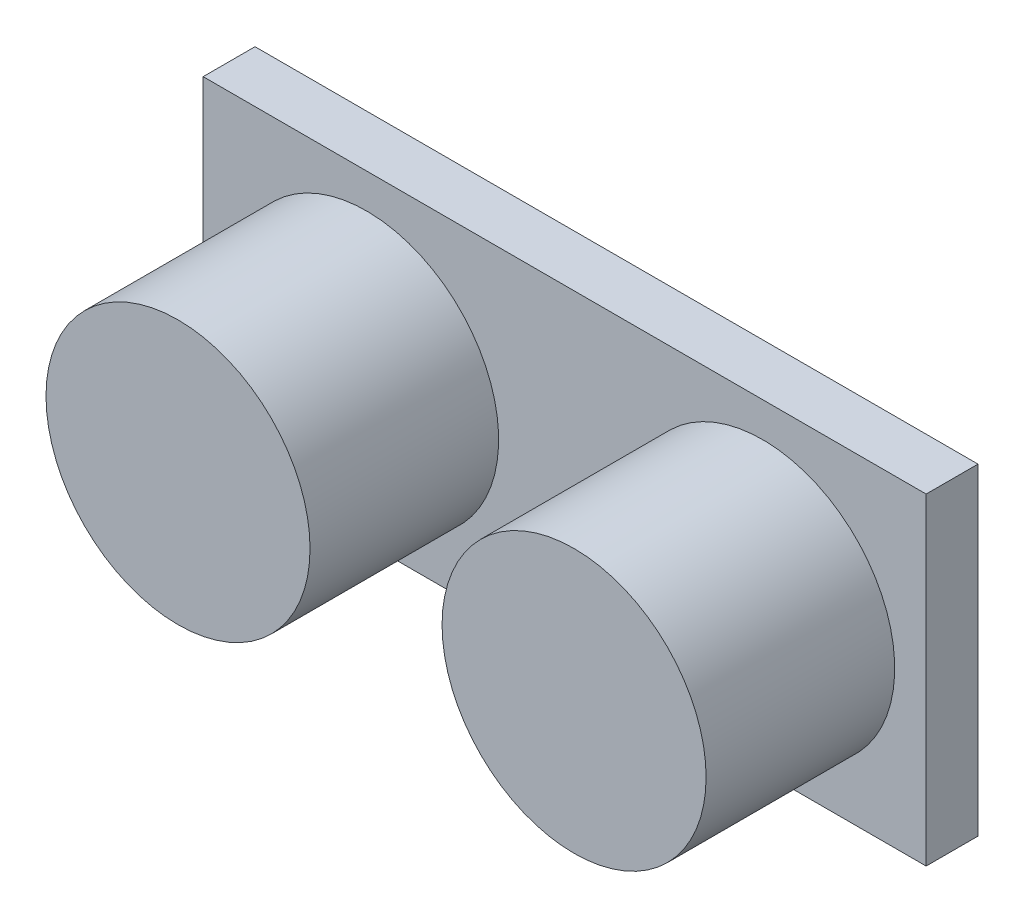
SolidWorks part; units mm, degrees
ref_plane "Front Plane" through (0, 0, 0) normal (0, 0, 1) x (1, 0, 0)
ref_plane "Top Plane" through (0, 0, 0) normal (0, 1, 0) x (1, 0, 0)
ref_plane "Right Plane" through (0, 0, 0) normal (1, 0, 0) x (0, 0, -1)
sketch "Sketch1" plane through (0, 0, 0) normal (0, 0, 1) x (1, 0, 0)
  line L1 (-23, -10.25) -> (23, -10.25)
  line L2 (-23, -10.25) -> (-23, 10.25)
  line L3 (-23, 10.25) -> (23, 10.25)
  line L4 (23, -10.25) -> (23, 10.25)
  line L5 (-23, -10.25) -> (23, 10.25) construction
  line L6 (-23, 10.25) -> (23, -10.25) construction
  point P0 (0, 0)
  dimension "D1" = 46
  dimension "D2" = 20.5
extrude "Boss-Extrude1" add sketch "Sketch1" along normal blind 3.3
sketch "Sketch2" plane through (0, 0, 3.3) normal (0, 0, 1) x (1, 0, 0)
  line L0 (-23, -0.35) -> (23, -0.35) construction
  line L1 (-23, 10.25) -> (-23, -10.25) construction
  line L2 (23, -10.25) -> (23, 10.25) construction
  line L3 (0, 0) -> (0, -0.35) construction
  line L4 (-12.6, -0.35) -> (0, 0) construction
  line L5 (0, 0) -> (12.6, -0.35) construction
  line L6 (23, 10.25) -> (-23, 10.25) construction
  circle A0 centre (-12.6, -0.35) radius 8.4
  circle A1 centre (12.6, -0.35) radius 8.4
  dimension "D1" = 25.2
  dimension "D2" = 16.8
  dimension "D3" = 10.6
extrude "Boss-Extrude2" add sketch "Sketch2" along normal blind 12
sketch "Sketch3" plane through (0, 0, 0) normal (0, 0, -1) x (-1, 0, 0)
  line L0 (0, 0) -> (0, -10.25) construction
  line L1 (23, -10.25) -> (-23, -10.25) construction
  line L2 (0, -10.25) -> (-2.6069, -14.263) construction
  line L4 (-5.15, -10.25) -> (5.15, -10.25)
  line L5 (-5.15, -10.25) -> (-5.15, -7.71)
  line L6 (-5.15, -7.71) -> (5.15, -7.71)
  line L7 (5.15, -10.25) -> (5.15, -7.71)
  line L8 (-5.15, -10.25) -> (5.15, -7.71) construction
  line L9 (-5.15, -7.71) -> (5.15, -10.25) construction
  point P5 (0, -8.98)
  dimension "D1" = 2.54
  dimension "D2" = 10.3
extrude "Boss-Extrude3" add sketch "Sketch3" along normal blind 2
